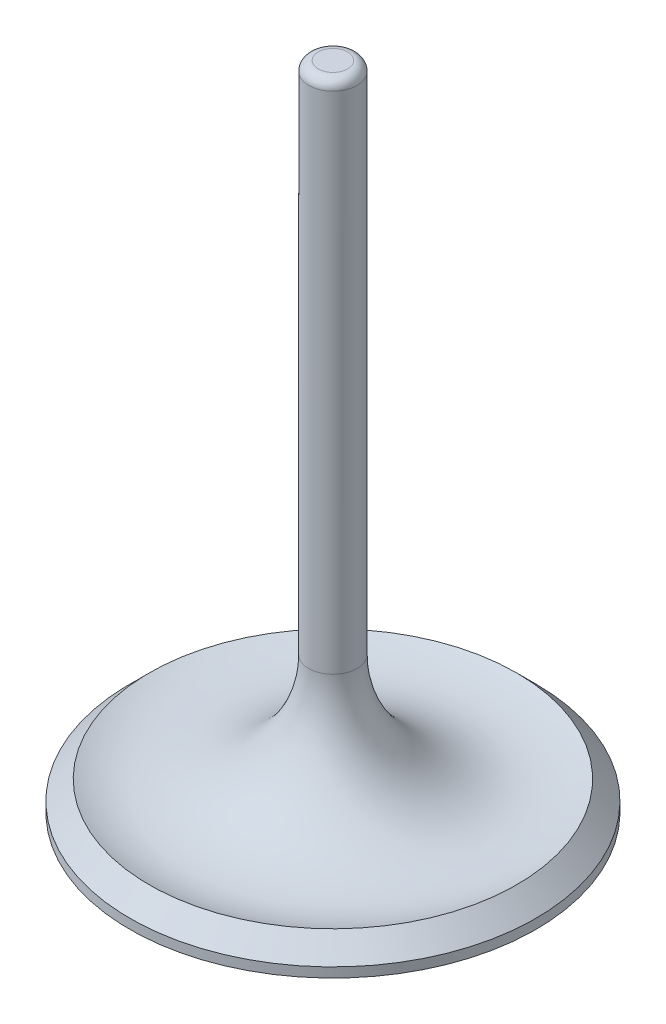
SolidWorks part; units mm, degrees
ref_plane "Front Plane" through (0, 0, 0) normal (0, 0, 1) x (1, 0, 0)
ref_plane "Top Plane" through (0, 0, 0) normal (0, 1, 0) x (1, 0, 0)
ref_plane "Right Plane" through (0, 0, 0) normal (1, 0, 0) x (0, 0, -1)
sketch "Sketch1" plane through (0, 0, 0) normal (1, 0, 0) x (0, 0, -1)
  line L0 (0, 0) -> (0, 85.55)
  line L1 (0, 85.55) -> (3.18, 85.55)
  line L2 (3.18, 85.55) -> (3.18, 17.9547)
  line L3 (24.13, 3.81) -> (26.67, 1.27)
  line L4 (26.67, 1.27) -> (26.67, 0)
  line L5 (26.67, 0) -> (0, 0)
  arc A0 (3.18, 17.9547) -> (24.13, 3.81) centre (18.43, 17.9547) ccw
  dimension "D1" = 85.55
  dimension "D6" = 15.25
  dimension "D2" = 3.18
  dimension "D3" = 26.67
  dimension "D4" = 1.27
  dimension "D5" = 3.81
  dimension "D7" = 45
revolve "Revolve1" add sketch "Sketch1" angle 360 about L0
fillet "Fillet1" radius 1.25 1 edges at (0, 85.55, -3.18)
